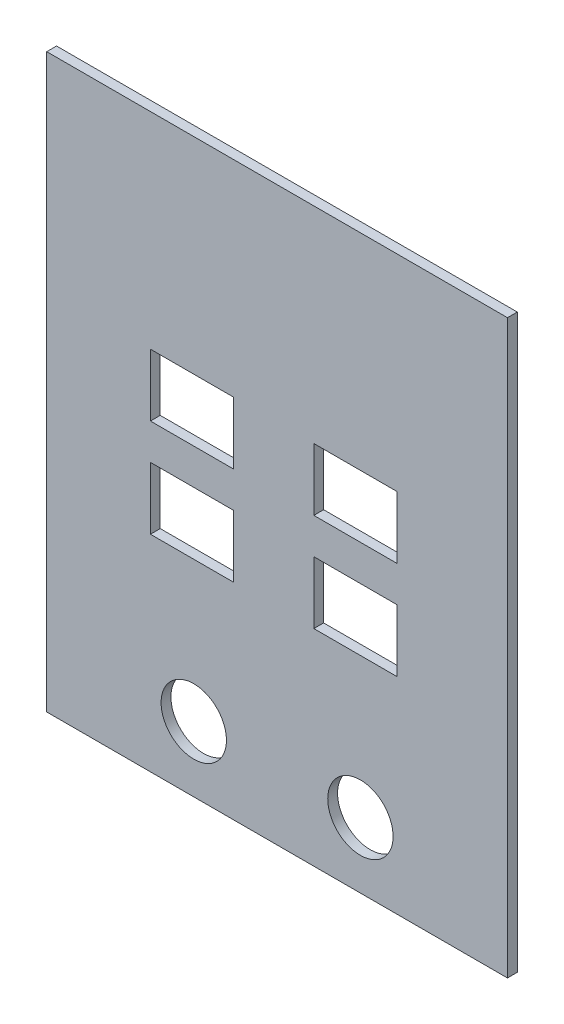
SolidWorks part; units mm, degrees
ref_plane "Front Plane" through (0, 0, 0) normal (0, 0, 1) x (1, 0, 0)
ref_plane "Top Plane" through (0, 0, 0) normal (0, 1, 0) x (1, 0, 0)
ref_plane "Right Plane" through (0, 0, 0) normal (1, 0, 0) x (0, 0, -1)
sketch "Sketch1" plane through (0, 0, 0) normal (0, 0, 1) x (1, 0, 0)
  line L0 (1.3302, 64.5142) -> (1.3302, -110.4858) construction
  line L1 (-69.1698, 64.5142) -> (71.8302, 64.5142)
  line L2 (-69.1698, 64.5142) -> (-69.1698, -110.4858)
  line L3 (-69.1698, -110.4858) -> (71.8302, -110.4858)
  line L4 (71.8302, 64.5142) -> (71.8302, -110.4858)
  line L5 (-69.1698, -22.9858) -> (71.8302, -22.9858) construction
  line L6 (-12.4846, -28.4608) -> (-12.4846, -47.5108)
  line L7 (37.5154, -28.4608) -> (37.5154, -47.5108)
  line L8 (12.1154, -28.4608) -> (37.5154, -28.4608)
  line L9 (12.1154, -28.4608) -> (12.1154, -47.5108)
  line L10 (-37.8846, -28.4608) -> (-12.4846, -28.4608)
  line L11 (-37.8846, -28.4608) -> (-37.8846, -47.5108)
  line L12 (-37.8846, -47.5108) -> (-12.4846, -47.5108)
  line L14 (12.1154, -47.5108) -> (37.5154, -47.5108)
  line L16 (37.5154, 1.5392) -> (37.5154, -17.5108)
  line L17 (12.1154, 1.5392) -> (37.5154, 1.5392)
  line L18 (12.1154, 1.5392) -> (12.1154, -17.5108)
  line L19 (12.1154, -17.5108) -> (37.5154, -17.5108)
  line L26 (-12.4846, 1.5392) -> (-12.4846, -17.5108)
  line L27 (-37.8846, 1.5392) -> (-12.4846, 1.5392)
  line L28 (-37.8846, 1.5392) -> (-37.8846, -17.5108)
  line L29 (-37.8846, -17.5108) -> (-12.4846, -17.5108)
  line L35 (-12.4846, 31.5392) -> (-12.4846, 12.4892) [skipped]
  line L36 (-37.8846, 31.5392) -> (-12.4846, 31.5392) [skipped]
  line L37 (-37.8846, 31.5392) -> (-37.8846, 12.4892) [skipped]
  line L38 (-37.8846, 12.4892) -> (-12.4846, 12.4892) [skipped]
  line L39 (37.5154, 31.5392) -> (37.5154, 12.4892) [skipped]
  line L40 (12.1154, 31.5392) -> (37.5154, 31.5392) [skipped]
  line L41 (12.1154, 31.5392) -> (12.1154, 12.4892) [skipped]
  line L42 (12.1154, 12.4892) -> (37.5154, 12.4892) [skipped]
  point P10 (0, 0)
  point P11 (0, 0)
  point P12 (37.5154, 1.5392)
  point P15 (0, 0)
  point P17 (37.5154, -22.9858)
  dimension "D1" = 141
  dimension "D2" = 175
  dimension "D3" = 2
  dimension "D4" = 3
extrude "Boss-Extrude1" add sketch "Sketch1" along normal blind 3 contours L4 L3 L2 L1
sketch "Sketch4" plane through (0, 0, 3) normal (0, 0, 1) x (1, 0, 0)
  line L0 (1.3302, 64.5142) -> (1.3302, -110.4858) construction
  line L1 (-69.1698, 64.5142) -> (71.8302, 64.5142) construction
  line L2 (-69.1698, -110.4858) -> (71.8302, -110.4858) construction
  line L3 (-69.1698, -22.9858) -> (71.8302, -22.9858) construction
  line L4 (-69.1698, 64.5142) -> (-69.1698, -110.4858) construction
  line L5 (71.8302, 64.5142) -> (71.8302, -110.4858) construction
  line L14 (12.5708, -28.4608) -> (37.9708, -28.4608)
  line L15 (12.5708, -28.4608) -> (12.5708, -47.5108)
  line L16 (12.5708, -47.5108) -> (37.9708, -47.5108)
  line L17 (37.9708, -28.4608) -> (37.9708, -47.5108)
  line L18 (12.5708, 1.5392) -> (37.9708, 1.5392)
  line L19 (12.5708, 1.5392) -> (12.5708, -17.5108)
  line L20 (12.5708, -17.5108) -> (37.9708, -17.5108)
  line L21 (37.9708, 1.5392) -> (37.9708, -17.5108)
  line L22 (-37.4292, -28.4608) -> (-12.0292, -28.4608)
  line L23 (-37.4292, -28.4608) -> (-37.4292, -47.5108)
  line L24 (-37.4292, -47.5108) -> (-12.0292, -47.5108)
  line L25 (-12.0292, -28.4608) -> (-12.0292, -47.5108)
  line L26 (-37.4292, 1.5392) -> (-12.0292, 1.5392)
  line L27 (-37.4292, 1.5392) -> (-37.4292, -17.5108)
  line L28 (-37.4292, -17.5108) -> (-12.0292, -17.5108)
  line L29 (-12.0292, 1.5392) -> (-12.0292, -17.5108)
extrude "Cut-Extrude1" cut sketch "Sketch4" against normal through all both and the other way through all
sketch "Sketch5" plane through (0, 0, 3) normal (0, 0, 1) x (1, 0, 0)
  line L0 (-69.1698, -110.4858) -> (71.8302, -110.4858) construction
  line L1 (-69.1698, 64.5142) -> (-69.1698, -110.4858) construction
  line L2 (1.3302, 64.5142) -> (1.3302, -110.4858) construction
  line L3 (-69.1698, 64.5142) -> (71.8302, 64.5142) construction
  circle A0 centre (-24.1698, -90.4858) radius 10
  circle A1 centre (26.8302, -90.4858) radius 10
  dimension "D1" = 20
  dimension "D2" = 20
  dimension "D3" = 45
extrude "Cut-Extrude2" cut sketch "Sketch5" against normal through all
sketch "Sketch7" plane through (0, 0, 3) normal (0, 0, 1) x (1, 0, 0)
  text T0 "NAME" font "Century Gothic" height 10
